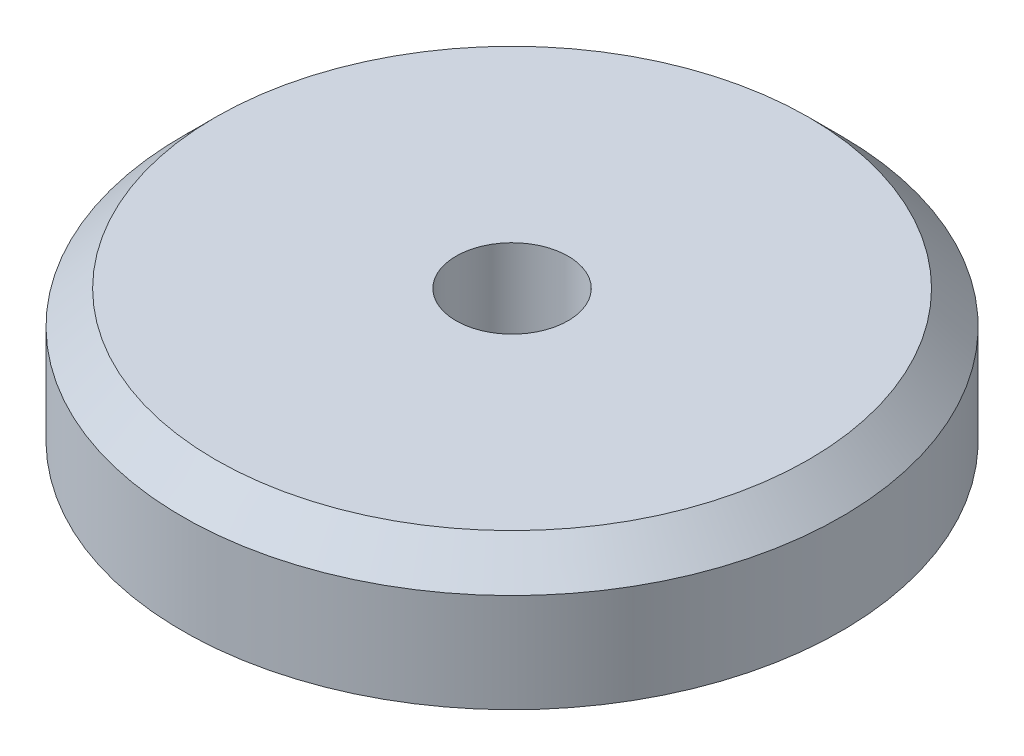
SolidWorks part; units mm, degrees
ref_plane "Front Plane" through (0, 0, 0) normal (0, 0, 1) x (1, 0, 0)
ref_plane "Top Plane" through (0, 0, 0) normal (0, 1, 0) x (1, 0, 0)
ref_plane "Right Plane" through (0, 0, 0) normal (1, 0, 0) x (0, 0, -1)
sketch "Sketch1" plane through (0, 0, 0) normal (0, 0, 1) x (1, 0, 0)
  line L0 (0, 0) -> (0, 11)
  line L1 (0, 11) -> (18, 11)
  line L2 (20, 9) -> (20, 3)
  line L3 (20, 3) -> (15.5, 3)
  line L4 (0, 0) -> (13.5, 0)
  line L5 (13.5, 0) -> (15.5, 3)
  line L6 (18, 11) -> (20, 9)
  point P4 (20, 11)
revolve "Revolve1" add sketch "Sketch1" angle 360 about L0
hole_wizard "M8 Tapped Hole1" positions "Sketch2" profile "Sketch3" tap size "M8" standard "ISO"
sketch "Sketch2" plane through (0, 11, 0) normal (0, 1, 0) x (1, 0, 0)
  point P0 (0, 0)
sketch "Sketch3" plane through (0, 11, 0) normal (1, 0, 0) x (0, 0, 1)
  line L0 (0, 0) -> (0, 21.25)
  line L1 (0, 21.25) -> (3.4, 21.25)
  line L2 (3.4, 21.25) -> (3.4, 0)
  line L5 (3.4, 0) -> (0, 0)
  line L10 (0, 21.25) -> (-3.4, 21.25) construction
  line L11 (0, -6.35) -> (0, 107.95) construction
  dimension "Tap Drill Dia." = 6.8
  dimension "Tap Drill Depth" = 21.25
  dimension "Drill Angle" = 180
cosmetic thread "Hole Thread1" parameters "D1"=15, "D2"=8
chamfer "Chamfer1" distance 1 angle 45 1 edges at (0, 0, -3.4)
